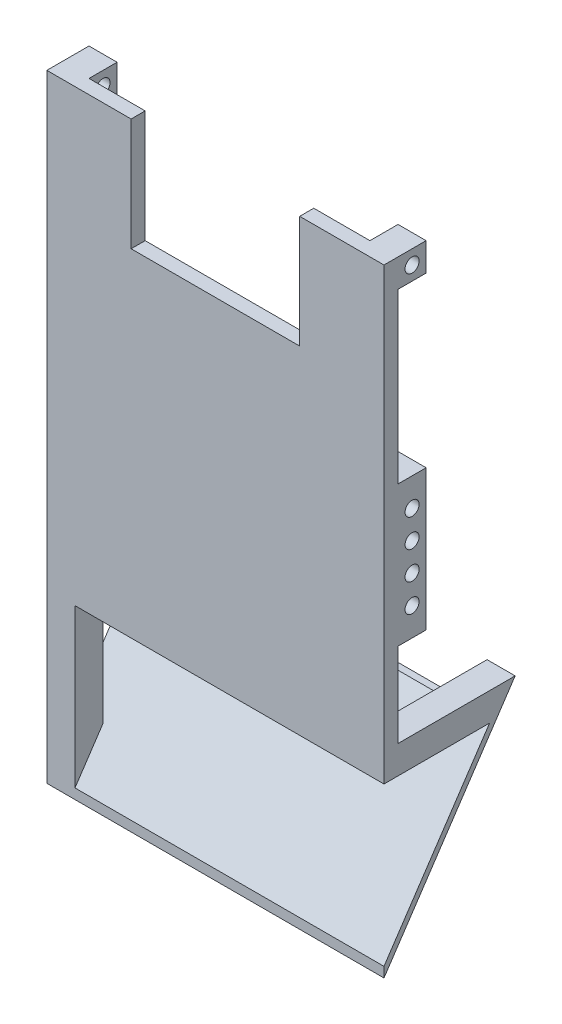
SolidWorks part; units mm, degrees
ref_plane "Front Plane" through (0, 0, 0) normal (0, 0, 1) x (1, 0, 0)
ref_plane "Top Plane" through (0, 0, 0) normal (0, 1, 0) x (1, 0, 0)
ref_plane "Right Plane" through (0, 0, 0) normal (1, 0, 0) x (0, 0, -1)
sketch "Sketch1" plane through (0, 0, 0) normal (0, 0, 1) x (1, 0, 0)
  line L1 (0, 0) -> (-152.4, 0)
  line L2 (0, 0) -> (0, 203.2)
  line L3 (0, 203.2) -> (-152.4, 203.2)
  line L4 (-152.4, 0) -> (-152.4, 203.2)
  dimension "D1" = 203.2
  dimension "D2" = 152.4
extrude "Boss-Extrude1" add sketch "Sketch1" along normal blind 6.35
sketch "Sketch2" plane through (0, 0, 6.35) normal (0, 0, 1) x (1, 0, 0)
  line L0 (0, 203.2) -> (-152.4, 203.2) construction
  line L1 (-114.3, 203.2) -> (-38.1, 203.2)
  line L2 (-114.3, 203.2) -> (-114.3, 152.4)
  line L3 (-114.3, 152.4) -> (-38.1, 152.4)
  line L4 (-38.1, 203.2) -> (-38.1, 152.4)
  line L5 (0, 0) -> (0, 203.2) construction
  line L6 (-152.4, 203.2) -> (-152.4, 0) construction
  dimension "D1" = 50.8
  dimension "D2" = 38.1
  dimension "D3" = 38.1
extrude "Cut-Extrude1" cut sketch "Sketch2" against normal through all and the other way through all
ref_plane "Plane1" through (-76.2, 0, 0) normal (-1, 0, 0) x (0, 0, 1)
sketch "Sketch3" plane through (0, 0, 0) normal (0, 0, -1) x (-1, 0, 0)
  line L1 (152.4, 203.2) -> (139.7, 203.2)
  line L2 (152.4, 203.2) -> (152.4, 190.5)
  line L3 (152.4, 190.5) -> (139.7, 190.5)
  line L4 (139.7, 203.2) -> (139.7, 190.5)
  line L5 (152.4, 203.2) -> (152.4, 0) construction
  line L6 (152.4, 50.8) -> (139.7, 50.8)
  line L7 (152.4, 50.8) -> (152.4, 114.3)
  line L8 (152.4, 114.3) -> (139.7, 114.3)
  line L9 (139.7, 50.8) -> (139.7, 114.3)
  dimension "D1" = 76.2
  dimension "D2" = 12.7
  dimension "D3" = 63.5
  dimension "D4" = 12.7
extrude "Boss-Extrude2" add sketch "Sketch3" along normal blind 12.7
sketch "Sketch4" plane through (-139.7, 0, 0) normal (1, 0, 0) x (0, 0, -1)
  line L0 (12.7, 203.2) -> (12.7, 190.5) construction
  line L1 (12.7, 203.2) -> (0, 203.2) construction
  line L2 (0, 114.3) -> (0, 50.8) construction
  line L3 (12.7, 114.3) -> (0, 114.3) construction
  circle A0 centre (6.35, 196.85) radius 3.175
  circle A1 centre (6.35, 101.6) radius 3.175
  circle A5 centre (6.35, 88.9) radius 3.175
  circle A6 centre (6.35, 76.2) radius 3.175
  circle A7 centre (6.35, 63.5) radius 3.175
  dimension "D1" = 6.35
  dimension "D2" = 6.35
  dimension "D4" = 6.35
  dimension "D3" = 6.35
  dimension "D6" = 6.35
  dimension "D7" = 12.7
  dimension "D8" = 12.7
  dimension "D5" = 4
extrude "Cut-Extrude2" cut sketch "Sketch4" against normal through all both and the other way through all
sketch "Sketch6" plane through (0, 0, 0) normal (1, 0, 0) x (0, 0, -1)
  line L0 (44.45, 0) -> (-6.35, -75.935)
  line L2 (41.394, 0) -> (-6.35, -71.3669)
  line L3 (-6.35, -71.3669) -> (-6.35, -75.935)
  line L4 (-6.35, 0) -> (-6.35, 203.2) construction
  line L8 (44.45, 0) -> (41.394, 0)
  dimension "D1" = 76.2
  dimension "D2" = 50.8
  dimension "D4" = 2.54
extrude "Boss-Extrude3" add sketch "Sketch6" against normal up to surface (152.4 mm away) separate body up to face at (-152.4, 196.85, -9.525)
sketch "Sketch11" plane through (0, 0, 0) normal (0, -1, 0) x (-1, 0, 0)
  line L1 (152.4, -6.35) -> (139.6749, -6.35)
  line L2 (152.4, -6.35) -> (152.4, 6.35)
  line L3 (152.4, 6.35) -> (139.6749, 6.35)
  line L4 (139.6749, -6.35) -> (139.6749, 6.35)
  dimension "D1" = 12.7
extrude "Boss-Extrude5" add sketch "Sketch11" along normal up to surface (71.3669 mm away)
sketch "Sketch13" plane through (0, 0, 0) normal (0, 0, -1) x (-1, 0, 0)
  line L1 (152.4, 0) -> (139.7, 0)
  line L2 (152.4, 0) -> (152.4, 12.7)
  line L3 (152.4, 12.7) -> (139.7, 12.7)
  line L4 (139.7, 0) -> (139.7, 12.7)
  dimension "D1" = 12.7
  dimension "D2" = 12.7
extrude "Boss-Extrude8" add sketch "Sketch13" along normal up to surface (44.45 mm away)
mirror "Mirror1" about plane through (-76.2, 0, 0) normal (-1, 0, 0) of "Cut-Extrude2", "Boss-Extrude2", "Boss-Extrude8"
